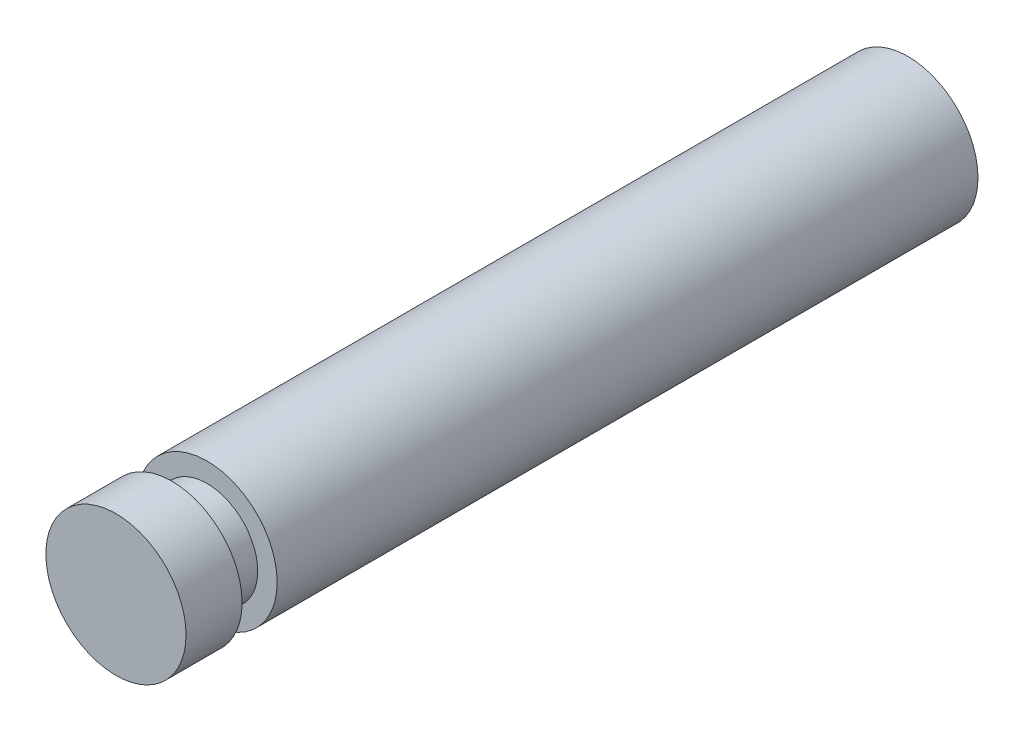
SolidWorks part; units mm, degrees
ref_plane "Front Plane" through (0, 0, 0) normal (0, 0, 1) x (1, 0, 0)
ref_plane "Top Plane" through (0, 0, 0) normal (0, 1, 0) x (1, 0, 0)
ref_plane "Right Plane" through (0, 0, 0) normal (1, 0, 0) x (0, 0, -1)
sketch "Sketch2" plane through (0, 0, 0) normal (0, 0, 1) x (1, 0, 0)
  circle A0 centre (0, 0) radius 1
  dimension "D1" = 2
extrude "Boss-Extrude1" add sketch "Sketch2" along normal blind 10
sketch "Sketch3" plane through (0, 0, 10) normal (0, 0, 1) x (1, 0, 0)
  circle A0 centre (0, 0) radius 0.7225
extrude "Boss-Extrude2" add sketch "Sketch3" along normal blind 0.5
sketch "Sketch4" plane through (0, 0, 10.5) normal (0, 0, 1) x (1, 0, 0)
  circle A0 centre (0, 0) radius 1
  dimension "D1" = 2
extrude "Boss-Extrude3" add sketch "Sketch4" along normal blind 0.8
